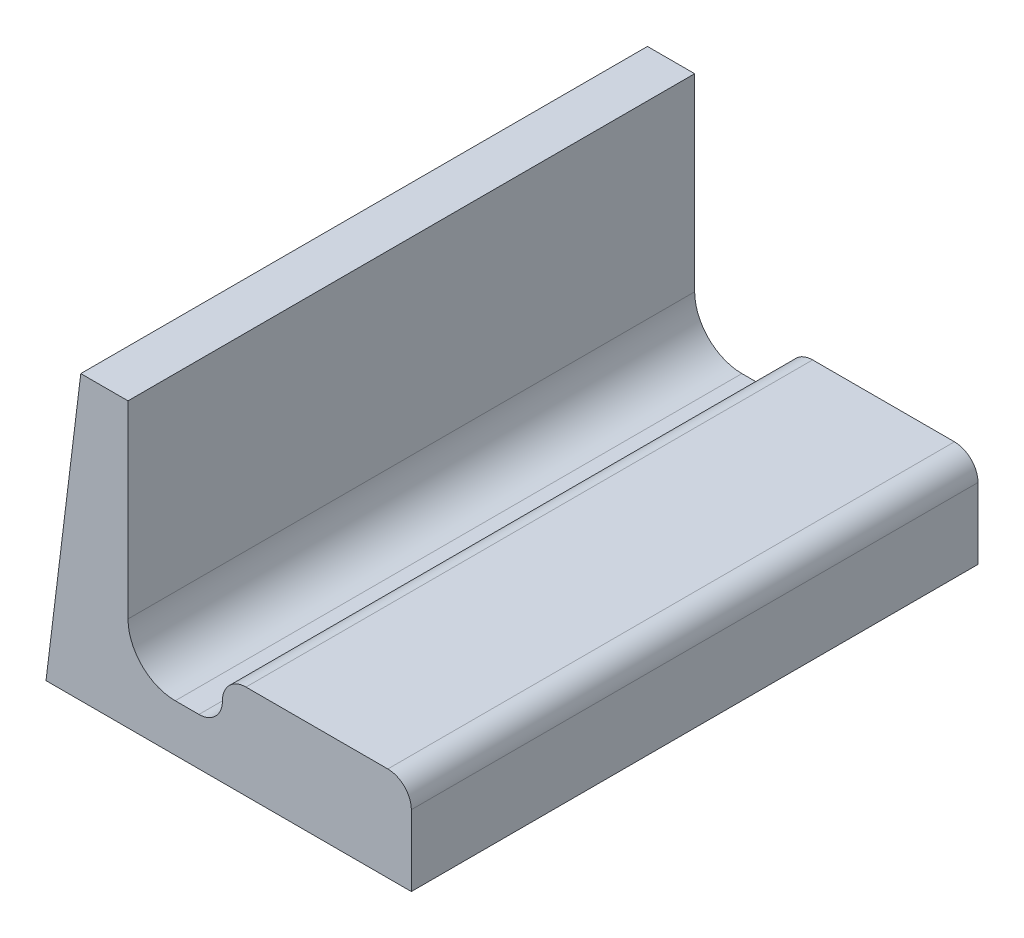
SolidWorks part; units mm, degrees
ref_plane "Front Plane" through (0, 0, 0) normal (0, 0, 1) x (1, 0, 0)
ref_plane "Top Plane" through (0, 0, 0) normal (0, 1, 0) x (1, 0, 0)
ref_plane "Right Plane" through (0, 0, 0) normal (1, 0, 0) x (0, 0, -1)
sketch "Sketch1" plane through (0, 0, 0) normal (0, 0, 1) x (1, 0, 0)
  line L0 (0, 0) -> (98.2562, 0)
  line L1 (98.2562, 0) -> (98.2562, 12.7)
  line L3 (22.0562, 25.4) -> (22.0562, 76.2)
  line L4 (22.0562, 76.2) -> (9.3562, 76.2)
  line L5 (9.3562, 76.2) -> (0, 0)
  line L6 (0, 0) -> (0, 76.2) construction
  line L7 (34.7562, 12.7) -> (41.1316, 12.7)
  line L8 (47.4562, 19.0246) -> (47.4562, 19.0754)
  line L9 (53.7808, 25.4) -> (91.9316, 25.4)
  line L10 (98.2562, 19.0754) -> (98.2562, 12.7)
  arc A0 (34.7562, 12.7) -> (22.0562, 25.4) centre (34.7562, 25.4) cw
  arc A1 (91.9316, 25.4) -> (98.2562, 19.0754) centre (91.9316, 19.0754) cw
  arc A2 (47.4562, 19.0754) -> (53.7808, 25.4) centre (53.7808, 19.0754) cw
  arc A3 (41.1316, 12.7) -> (47.4562, 19.0246) centre (41.1316, 19.0246) ccw
  point P12 (22.0562, 12.7)
  point P16 (98.2562, 25.4)
  point P19 (47.4562, 25.4)
  point P22 (104.7749, 19.0754)
  dimension "D6" = 12.7
  dimension "D8" = 6.3246
  dimension "D1" = 7
  dimension "D2" = 12.7
  dimension "D3" = 12.7
  dimension "D4" = 50.8
  dimension "D5" = 76.2
  dimension "D7" = 12.7
  dimension "D9" = 25.4
extrude "Boss-Extrude1" add sketch "Sketch1" along normal blind 152.4
